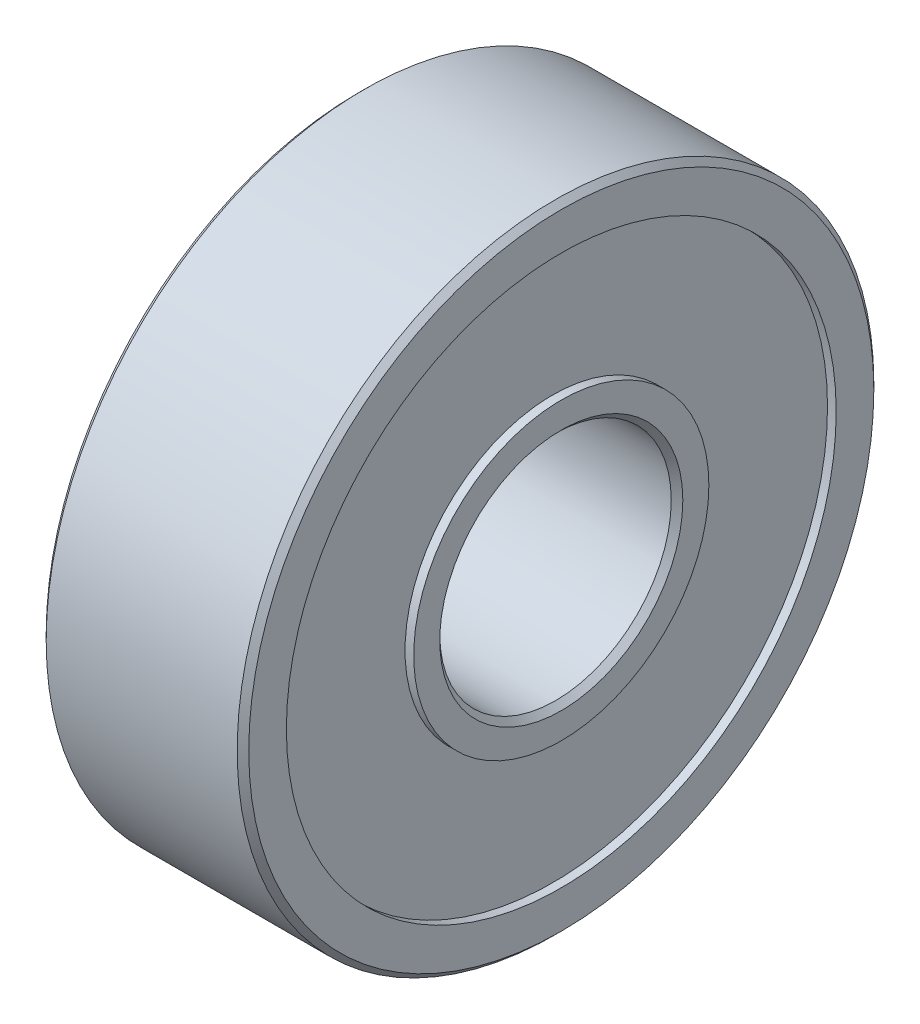
SolidWorks part; units mm, degrees
material "Plain Carbon Steel"
ref_plane "Front Plane" through (0, 0, 0) normal (0, 0, 1) x (1, 0, 0)
ref_plane "Top Plane" through (0, 0, 0) normal (0, 1, 0) x (1, 0, 0)
ref_plane "Right Plane" through (0, 0, 0) normal (1, 0, 0) x (0, 0, -1)
sketch "Sketch1" plane through (0, 0, 0) normal (0, 0, 1) x (1, 0, 0)
  line L0 (3.5, 4) -> (-3.5, 4)
  line L1 (-3.5, 4) -> (-3.5, 5.1)
  line L2 (-3.5, 5.1) -> (-3.2, 5.1)
  line L3 (-3.2, 5.1) -> (-3.2, 9.5)
  line L4 (-3.2, 9.5) -> (-3.5, 9.5)
  line L5 (-3.5, 9.5) -> (-3.5, 11)
  line L6 (-3.5, 11) -> (3.5, 11)
  line L7 (0, 11) -> (0, 4) construction
  line L8 (3.5, 9.5) -> (3.5, 11)
  line L9 (3.2, 9.5) -> (3.5, 9.5)
  line L10 (3.2, 5.1) -> (3.2, 9.5)
  line L11 (3.5, 5.1) -> (3.2, 5.1)
  line L12 (3.5, 4) -> (3.5, 5.1)
  line L13 (0, 0) -> (-4.3663, 0) construction
  dimension "D1" = 8
  dimension "D2" = 22
  dimension "D3" = 7
  dimension "D4" = 10.2
  dimension "D5" = 1.5
  dimension "D6" = 0.3
revolve "Revolve1" add sketch "Sketch1" angle 360 about L13
chamfer "Chamfer1" distance 0.2 angle 45 4 edges at (-3.5, 0, -4) (3.5, 0, -4) (-3.5, 0, -11) (3.5, 0, -11)
